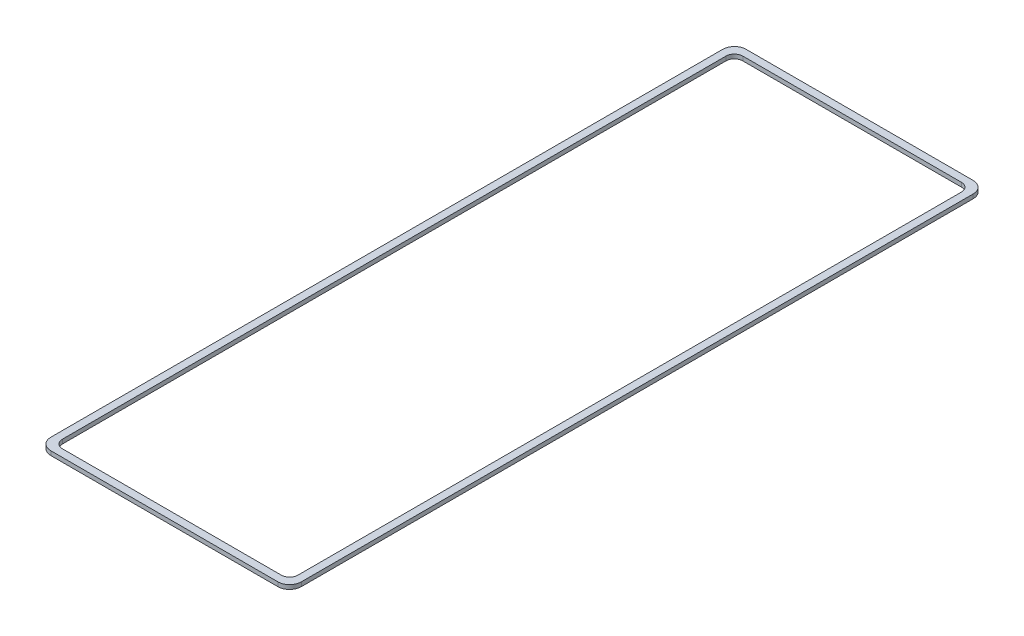
SolidWorks part; units mm, degrees
material "PC High Viscosity"
ref_plane "Front Plane" through (0, 0, 0) normal (0, 0, 1) x (1, 0, 0)
ref_plane "Top Plane" through (0, 0, 0) normal (0, 1, 0) x (1, 0, 0)
ref_plane "Right Plane" through (0, 0, 0) normal (1, 0, 0) x (0, 0, -1)
sketch "Sketch1" plane through (0, 0, 0) normal (0, 1, 0) x (1, 0, 0)
  line L6 (339.725, 942.975) -> (-339.725, 942.975)
  line L14 (339.725, 942.975) -> (339.725, -942.975)
  line L15 (339.725, -942.975) -> (-339.725, -942.975)
  line L16 (-339.725, 942.975) -> (-339.725, -942.975)
  line L17 (339.725, 942.975) -> (-339.725, -942.975) construction
  line L18 (339.725, -942.975) -> (-339.725, 942.975) construction
  point P0 (0, 0)
  point P1 (0, 0)
  dimension "D2" = 1885.95
  dimension "D3" = 679.45
extrude "Boss-Extrude1" add sketch "Sketch1" along normal blind 11.43
sketch "Sketch3" plane through (0, 11.43, 0) normal (0, 1, 0) x (1, 0, 0)
  line L8 (-319.405, 922.655) -> (-319.405, -922.655)
  line L9 (-319.405, -922.655) -> (319.405, -922.655)
  line L10 (319.405, -922.655) -> (319.405, 922.655)
  line L11 (319.405, 922.655) -> (-319.405, 922.655)
  line L12 (-319.405, 922.655) -> (-319.405, -922.655)
  line L13 (-319.405, -922.655) -> (319.405, -922.655)
  line L14 (319.405, -922.655) -> (319.405, 922.655)
  line L15 (319.405, 922.655) -> (-319.405, 922.655)
  dimension "D1" = 20.32
extrude "Cut-Extrude2" cut sketch "Sketch3" against normal through all
fillet "Fillet1" radius 31.75 4 edges at (339.725, 5.715, -942.975) (339.725, 5.715, 942.975) (-339.725, 5.715, 942.975) (-339.725, 5.715, -942.975)
fillet "Fillet2" radius 22.86 4 edges at (-319.405, 5.715, -922.655) (319.405, 5.715, -922.655) (319.405, 5.715, 922.655) (-319.405, 5.715, 922.655)
